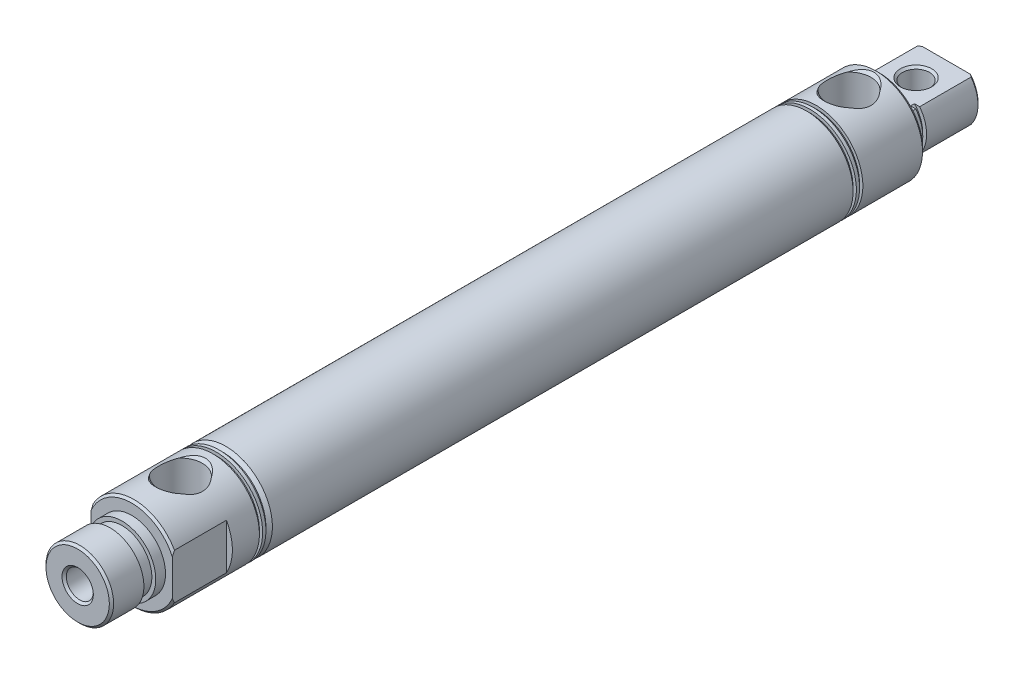
SolidWorks part; units mm, degrees
material "AISI 316 Stainless Steel Sheet (SS)"
ref_plane "Front" through (0, 0, 0) normal (0, 0, 1) x (1, 0, 0)
ref_plane "Top" through (0, 0, 0) normal (0, 1, 0) x (1, 0, 0)
ref_plane "Right" through (0, 0, 0) normal (1, 0, 0) x (0, 0, -1)
sketch "Sketch1" plane through (0, 0, 0) normal (0, 0, 1) x (1, 0, 0)
  circle A0 centre (0, 0) radius 10.922
  dimension "E" = 21.844
extrude "Extrude1" add sketch "Sketch1" along normal up to surface (95.631 mm away) and the other way up to surface (95.631 mm away)
ref_plane "SwitchPlaneA" through (0, 0, 57.779) normal (0, 0, 1) x (1, 0, 0)
ref_plane "SwitchPlaneB" through (0, 0, -44.669) normal (0, 0, -1) x (-1, 0, 0)
sketch "Sketch2" plane through (0, 0, 0) normal (1, 0, 0) x (0, 0, -1)
  line L0 (0, 0) -> (-79.7053, 0) construction
  line L1 (-95.631, 7.9248) -> (-97.917, 7.9248)
  line L2 (-95.631, 10.922) -> (-95.631, -10.922) construction
  line L3 (-97.917, 7.9248) -> (-97.917, 7)
  line L4 (-100.717, 7.9375) -> (-108.331, 7.9375)
  line L5 (-108.331, 7.9375) -> (-108.331, 0)
  line L6 (-108.331, 0) -> (-95.631, 0)
  line L7 (-95.631, 0) -> (-95.631, 7.9248)
  line L8 (-100.717, 7.9375) -> (-100.717, 7)
  line L9 (-100.717, 7) -> (-97.917, 7)
  dimension "D1" = 2.286
  dimension "NN" = 15.875
  dimension "B" = 15.8496
  dimension "D2" = 14
  dimension "W-K" = 12.7
  dimension "D3" = 2.8
revolve "Nose" add sketch "Sketch2" angle 360 about L0
sketch "Sketch3" plane through (0, 0, 0) normal (1, 0, 0) x (0, 0, -1)
  line L0 (0, 0) -> (-66.9635, 0) construction
  line L1 (95.631, 10.922) -> (-95.631, 10.922) construction
  line L2 (-76.581, 10.922) -> (-75.819, 10.922)
  line L3 (-76.581, 10.922) -> (-76.581, 10.16)
  line L4 (-76.581, 10.16) -> (-75.819, 10.16)
  line L5 (-75.819, 10.922) -> (-75.819, 10.16)
  line L6 (-75.057, 10.922) -> (-75.057, 10.16)
  line L7 (-75.057, 10.16) -> (-74.295, 10.16)
  line L8 (-74.295, 10.16) -> (-73.533, 10.922)
  line L9 (-73.533, 10.922) -> (-75.057, 10.922)
  line L10 (65.107, 10.922) -> (65.107, 10.16)
  line L11 (65.107, 10.16) -> (64.345, 10.922)
  line L12 (64.345, 10.922) -> (65.107, 10.922)
  line L13 (63.583, 10.922) -> (63.583, 10.16)
  line L14 (63.583, 10.16) -> (62.821, 10.922)
  line L15 (62.821, 10.922) -> (63.583, 10.922)
  line L16 (-95.631, 10.922) -> (-95.631, -10.922) construction
  line L17 (95.631, -10.922) -> (95.631, 10.922) construction
  dimension "D1" = 0.762
  dimension "D2" = 30.524
  dimension "D3" = 19.05
  dimension "D4" = 0.762
  dimension "D5" = 45
  dimension "D6" = 1.524
  dimension "D7" = 0.762
revolve "CoverGrooves" cut sketch "Sketch3" angle 360 about L0
sketch "Sketch7" plane through (0, 0, 0) normal (1, 0, 0) x (0, 0, -1)
  line L0 (-84.201, 0) -> (-84.201, 19.911) construction
  line L1 (-84.201, 10.922) -> (-78.351, 10.922)
  line L2 (-76.581, 10.922) -> (-95.631, 10.922) construction
  line L3 (-78.351, 10.922) -> (-79.051, 10.222)
  line L4 (-79.051, 10.222) -> (-79.051, 0)
  line L5 (-79.051, 0) -> (-84.201, 0)
  line L6 (-84.201, 0) -> (-84.201, 10.922)
  line L7 (-108.331, 7.9375) -> (-108.331, -7.9375) construction
  line L8 (-73.533, 10.922) -> (-74.295, 10.16) construction
  dimension "D1" = 10.3
  dimension "D2" = 0.7
  dimension "Y-K" = 24.13
revolve "FrontPort" cut sketch "Sketch7" angle 360 about L0
sketch "Sketch8" plane through (0, 0, 108.331) normal (0, 0, 1) x (1, 0, 0)
  circle A0 centre (0, 0) radius 3.175
  dimension "MM" = 6.35
extrude "RodHole" cut sketch "Sketch8" against normal up to surface (161.631 mm away)
sketch "Sketch9" plane through (0, 0, -53.3) normal (0, 0, 1) x (1, 0, 0)
  circle A0 centre (0, 0) radius 9.525
  dimension "Bore" = 19.05
extrude "StrokeChamber" cut sketch "Sketch9" along normal up to surface (106.6 mm away)
chamfer "Chamfer1" distance 0.5 angle 45 4 edges at (10.922, 0, -95.631) (10.922, 0, 95.631) (-7.9375, 0, 108.331) (3.175, 0, 108.331)
sketch "Sketch4" plane through (0, 0, 0) normal (0, 1, 0) x (1, 0, 0)
  line L0 (0, 0) -> (0, 54.4802) construction
  line L2 (10.922, -95.631) -> (9.525, -95.631)
  line L3 (10.922, -95.631) -> (10.922, -82.931)
  line L4 (10.922, -82.931) -> (9.525, -82.931)
  line L5 (9.525, -95.631) -> (9.525, -82.931)
  line L6 (10.922, 92.583) -> (10.422, 92.583)
  line L7 (10.922, 92.583) -> (10.922, 95.631)
  line L8 (10.922, 95.631) -> (10.422, 95.631)
  line L9 (10.422, 92.583) -> (10.422, 95.631)
  line L10 (-10.922, 0) -> (10.922, 0) construction
  line L11 (-10.922, -95.631) -> (10.922, -95.631) construction
  line L12 (10.922, 95.631) -> (-10.922, 95.631) construction
  line L13 (-10.422, 92.583) -> (-10.422, 95.631)
  line L14 (-10.922, 95.631) -> (-10.422, 95.631)
  line L15 (-10.922, 92.583) -> (-10.922, 95.631)
  line L16 (-10.922, 92.583) -> (-10.422, 92.583)
  line L17 (-9.525, -95.631) -> (-9.525, -82.931)
  line L18 (-10.922, -82.931) -> (-9.525, -82.931)
  line L19 (-10.922, -95.631) -> (-10.922, -82.931)
  line L20 (-10.922, -95.631) -> (-9.525, -95.631)
  line L21 (-10.922, 0) -> (10.922, 0) construction
  dimension "D1" = 12.7
  dimension "NC" = 20.844
  dimension "N" = 19.05
  dimension "NE" = 3.048
extrude "Flats" cut sketch "Sketch4" against normal through all and the other way through all
sketch "Sketch10" [suppressed] plane through (0, 0, 0) normal (1, 0, 0) x (0, 0, -1)
  line L0 (0, 0) -> (-22.9719, 0) construction
  line L1 (200.152, 0) -> (200.152, 5.85)
  line L2 (200.152, 5.85) -> (199.452, 5.15)
  line L3 (199.452, 5.15) -> (0, 5.15)
  line L4 (0, 5.15) -> (0, 0)
  line L5 (0, 0) -> (200.152, 0)
  line L6 (-178.054, 10.922) -> (-178.816, 10.16) construction
  line L8 (200.152, -10.922) -> (200.152, 10.922) construction
  dimension "D1" = 10.3
  dimension "D2" = 0.7
revolve "RearStdPort" [suppressed] cut sketch "Sketch10" angle 360 about L0
sketch "Sketch11" plane through (0, 0, 0) normal (1, 0, 0) x (0, 0, -1)
  line L0 (0, 0) -> (65.1253, 0) construction
  line L1 (95.631, 7.4375) -> (95.131, 7.9375)
  line L2 (95.131, 7.9375) -> (83.07, 7.9375)
  line L3 (83.07, 7.9375) -> (83.07, 7)
  line L4 (83.07, 7) -> (82.169, 7)
  line L5 (82.169, 7) -> (82.169, 7.9375)
  line L6 (82.169, 7.9375) -> (79.883, 7.9375)
  line L7 (79.883, 7.9375) -> (79.883, 10.16)
  line L8 (79.883, 10.16) -> (79.121, 10.922)
  line L9 (62.821, 10.922) -> (-73.533, 10.922) construction
  line L10 (79.121, 10.922) -> (95.631, 10.922)
  line L11 (95.631, 7.4375) -> (95.631, 10.922)
  line L16 (65.107, 10.16) -> (64.345, 10.922) construction
  line L17 (95.631, -10.922) -> (95.631, 10.922) construction
  dimension "D1" = 0.901
  dimension "D2" = 2.286
  dimension "D3" = 15.875
  dimension "ZB-LB+L" = 15.748
  dimension "D4" = 14
revolve "EndThreads" cut sketch "Sketch11" angle 360 about L0
sketch "Sketch13" plane through (0, 0, 0) normal (1, 0, 0) x (0, 0, -1)
  line L0 (72.771, 0) -> (72.771, 52.324) construction
  line L1 (72.771, 0) -> (77.921, 0)
  line L2 (77.921, 0) -> (77.921, 10.222)
  line L3 (77.921, 10.222) -> (78.621, 10.922)
  line L5 (78.621, 10.922) -> (72.771, 10.922)
  line L6 (72.771, 10.922) -> (72.771, 0)
  line L10 (95.631, -7.4375) -> (95.631, 7.4375) construction
  line L11 (-73.533, 10.922) -> (-75.057, 10.922) construction
  line L12 (-79.051, 0) -> (-84.201, 0) construction
  line L13 (-78.351, 10.922) -> (-79.051, 10.222) construction
  dimension "D1" = 22.86
revolve "RearTopPort" cut sketch "Sketch13" angle 360 about L0
sketch "Sketch12" plane through (0, 0, 0) normal (1, 0, 0) x (0, -1, 0)
  line L0 (0, 0) -> (0, 62.5586) construction
  line L1 (7.4375, 95.631) -> (-7.4375, 95.631) construction
  line L2 (10.922, 95.631) -> (4.826, 95.631)
  line L3 (10.922, 95.631) -> (10.922, 80.607)
  line L4 (10.922, 80.607) -> (4.826, 80.607)
  line L5 (4.826, 95.631) -> (4.826, 80.607)
  line L6 (-10.922, 0) -> (10.922, 0) construction
  line L7 (-4.826, 95.631) -> (-4.826, 80.607)
  line L8 (-10.922, 80.607) -> (-4.826, 80.607)
  line L9 (-10.922, 95.631) -> (-10.922, 80.607)
  line L10 (-10.922, 95.631) -> (-4.826, 95.631)
  line L12 (-10.922, 0) -> (10.922, 0) construction
  dimension "D1" = 15.024
  dimension "F" = 9.652
extrude "EndFlats" cut sketch "Sketch12" against normal through all and the other way through all
sketch "Sketch15" plane through (0, 0, 0) normal (1, 0, 0) x (0, -1, 0)
  line L0 (0, 88.519) -> (21.0846, 88.519) construction
  line L1 (4.826, 92.2067) -> (4.326, 91.7067)
  line L2 (4.826, 95.131) -> (4.826, 83.07) construction
  line L3 (4.326, 91.7067) -> (-4.326, 91.7067)
  line L4 (-4.326, 91.7067) -> (-4.826, 92.2067)
  line L5 (-4.826, 83.07) -> (-4.826, 95.131) construction
  line L6 (-4.826, 92.2067) -> (-4.826, 88.519)
  line L7 (-4.826, 88.519) -> (4.826, 88.519)
  line L8 (4.826, 88.519) -> (4.826, 92.2067)
  line L9 (10.16, 79.883) -> (-10.16, 79.883) construction
  dimension "D1" = 0.5
  dimension "G" = 6.3754
  dimension "L" = 8.636
revolve "ClevisPinHole" cut sketch "Sketch15" angle 360 about L0
sketch "Sketch18" plane through (0, 0, 0) normal (1, 0, 0) x (0, 0, -1)
  line L0 (88.519, 0) -> (88.519, 25.8254) construction
  line L2 (88.519, 0) -> (88.519, -21.0846) construction
  line L3 (88.519, 9.525) -> (91.2067, 9.525)
  line L4 (91.2067, 9.525) -> (91.7067, 9.025)
  line L5 (91.7067, 9.025) -> (91.7067, -9.025)
  line L6 (91.7067, -9.025) -> (91.2067, -9.525)
  line L7 (91.2067, -9.525) -> (88.519, -9.525)
  line L8 (88.519, -9.525) -> (88.519, 9.525)
  line L9 (91.7067, -4.326) -> (91.7067, 4.326) construction
  point P13 (88.519, 0)
  dimension "D1" = 0.5
  dimension "GB" = 19.05
revolve "ClevisPin" [suppressed] add sketch "Sketch18" angle 360 about L0
ref_plane "Plane1" through (0, 10.222, 0) normal (0, 1, 0) x (-1, 0, 0)
